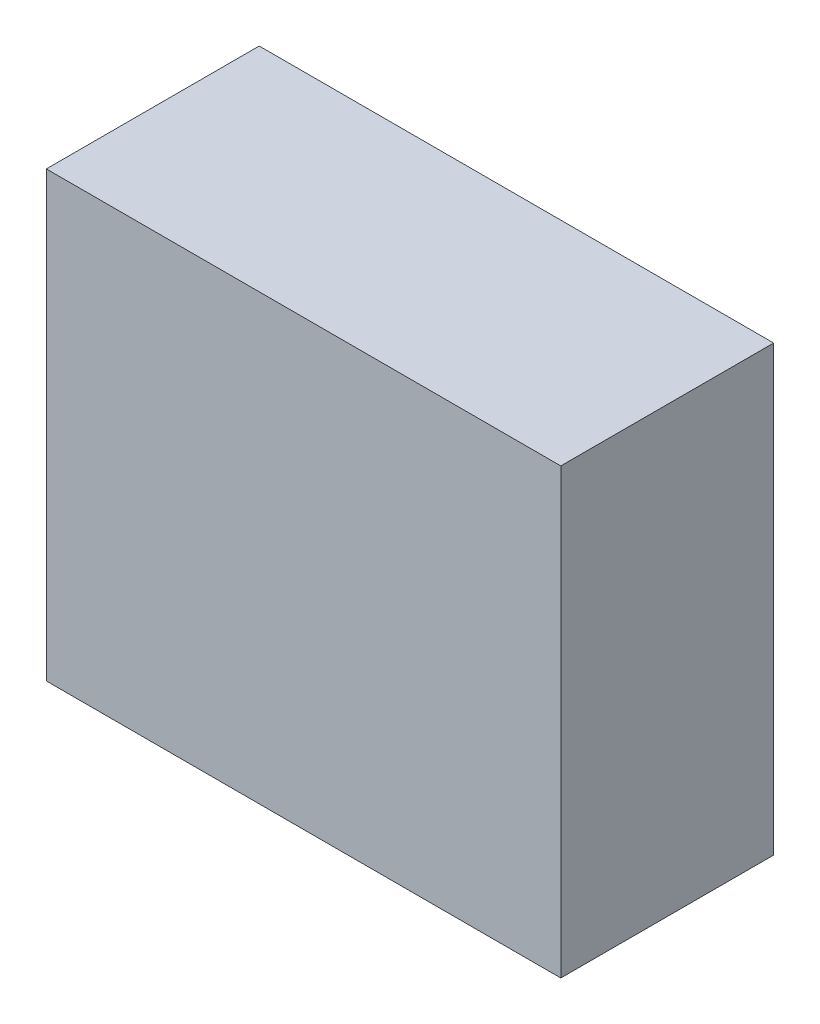
SolidWorks part; units mm, degrees
ref_plane "Front Plane" through (0, 0, 0) normal (0, 0, 1) x (1, 0, 0)
ref_plane "Top Plane" through (0, 0, 0) normal (0, 1, 0) x (1, 0, 0)
ref_plane "Right Plane" through (0, 0, 0) normal (1, 0, 0) x (0, 0, -1)
sketch "Sketch1" plane through (0, 0, 0) normal (0, 1, 0) x (1, 0, 0)
  line L1 (0, 0) -> (29, 0)
  line L2 (0, 0) -> (0, 12)
  line L3 (0, 12) -> (29, 12)
  line L4 (29, 0) -> (29, 12)
  dimension "D1" = 12
  dimension "D2" = 29
extrude "Boss-Extrude1" add sketch "Sketch1" along normal blind 25
